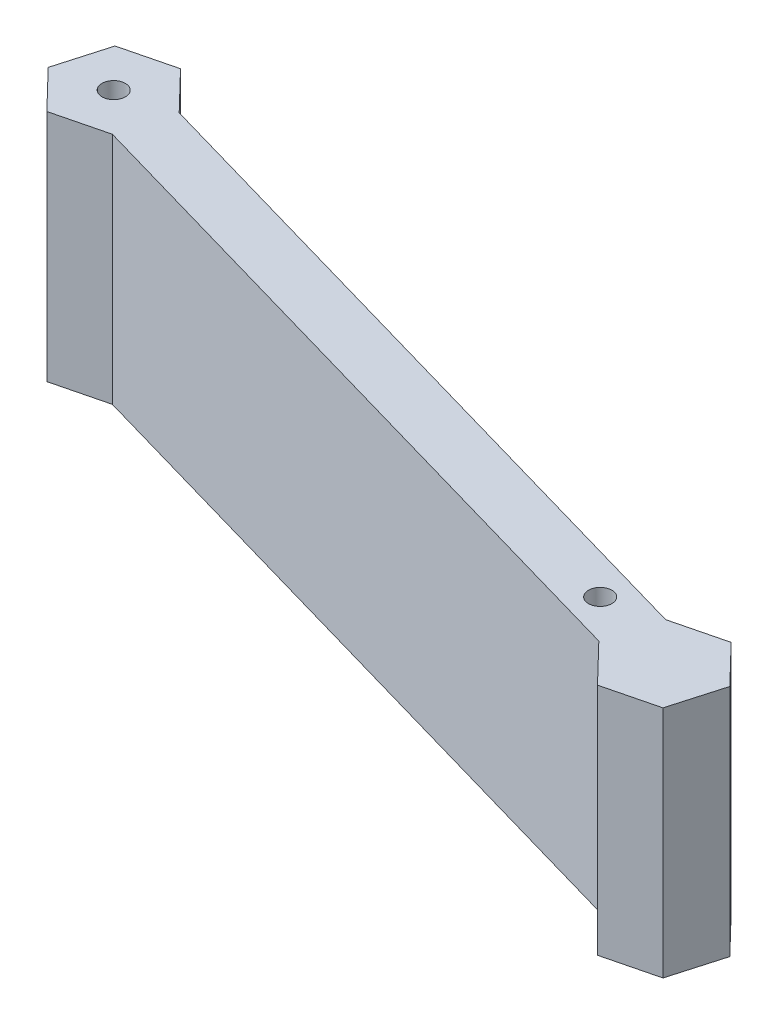
SolidWorks part; units mm, degrees
material "ABS"
ref_plane "Plano frontal" through (0, 0, 0) normal (0, 0, 1) x (1, 0, 0)
ref_plane "Plano superior" through (0, 0, 0) normal (0, 1, 0) x (1, 0, 0)
ref_plane "Plano direito" through (0, 0, 0) normal (1, 0, 0) x (0, 0, -1)
sketch "Esboço1" plane through (0, 0, 0) normal (0, 1, 0) x (1, 0, 0)
  line L1 (4.8123, -4.9842) -> (6.7226, 1.6755)
  line L2 (6.7226, 1.6755) -> (1.9103, 6.6596)
  line L3 (1.9103, 6.6596) -> (-4.8123, 4.9842)
  line L4 (-4.8123, 4.9842) -> (-6.7226, -1.6755)
  line L5 (-6.7226, -1.6755) -> (-1.9103, -6.6596)
  line L6 (-1.9103, -6.6596) -> (4.8123, -4.9842)
  circle A0 centre (0, 0) radius 6 construction
extrude "Ressalto-extrusão1" add sketch "Esboço1" along normal blind 30
sketch "Esboço2" plane through (0, 0, 0) normal (0, -1, 0) x (1, 0, 0)
  circle A0 centre (0, 0) radius 1.5
extrude "Corte-extrusão1" cut sketch "Esboço2" against normal blind 30
sketch "Esboço4" plane through (5.7674, 0, 1.6543) normal (0.9612, 0, 0.2757) x (0.2757, 0, -0.9612)
  line L1 (3.4641, 0) -> (-3.4641, 0)
  line L2 (3.4641, 0) -> (3.4641, 30)
  line L3 (3.4641, 30) -> (-3.4641, 30)
  line L4 (-3.4641, 0) -> (-3.4641, 30)
extrude "Ressalto-extrusão2" add sketch "Esboço4" along normal blind 91
sketch "Esboço5" plane through (0, 0, 0) normal (0, 1, 0) x (1, 0, 0)
  line L0 (92.2849, -30.0749) -> (94.1951, -23.4153) construction
  line L1 (105.73, -26.7239) -> (100.9177, -21.7398)
  line L2 (100.9177, -21.7398) -> (94.1951, -23.4153)
  line L3 (94.1951, -23.4153) -> (92.2849, -30.0749)
  line L4 (92.2849, -30.0749) -> (97.0972, -35.0591)
  line L5 (97.0972, -35.0591) -> (103.8197, -33.3836)
  line L6 (103.8197, -33.3836) -> (105.73, -26.7239)
  circle A0 centre (99.0074, -28.3994) radius 6 construction
  point P10 (0, 0)
  dimension "D1" = 12
  dimension "D2" = 0
  dimension "D3" = 0
extrude "Ressalto-extrusão3" add sketch "Esboço5" along normal through all
ref_plane "Plano1" through (43.7363, 0, 12.5454) normal (-0.9612, 0, -0.2757) x (-0.2757, 0, 0.9612)
mirror "Espelhar1" about plane through (43.7363, 0, 12.5454) normal (-0.9612, 0, -0.2757) of "Corte-extrusão1"
